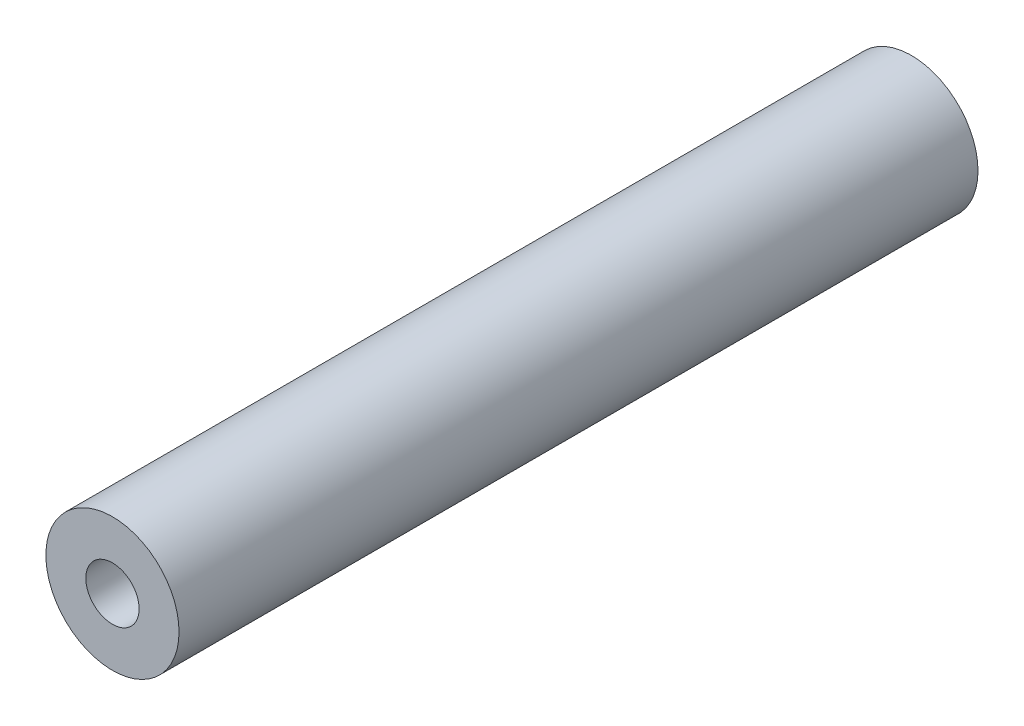
SolidWorks part; units mm, degrees
ref_plane "Plano frontal" through (0, 0, 0) normal (0, 0, 1) x (1, 0, 0)
ref_plane "Plano superior" through (0, 0, 0) normal (0, 1, 0) x (1, 0, 0)
ref_plane "Plano direito" through (0, 0, 0) normal (1, 0, 0) x (0, 0, -1)
sketch "Esboço1" plane through (0, 0, 0) normal (0, 0, 1) x (1, 0, 0)
  circle A0 centre (0, 0) radius 5
  circle A1 centre (0, 0) radius 2
  dimension "D1" = 10
  dimension "D2" = 4
extrude "Ressalto-extrusão1" add sketch "Esboço1" along normal blind 60
